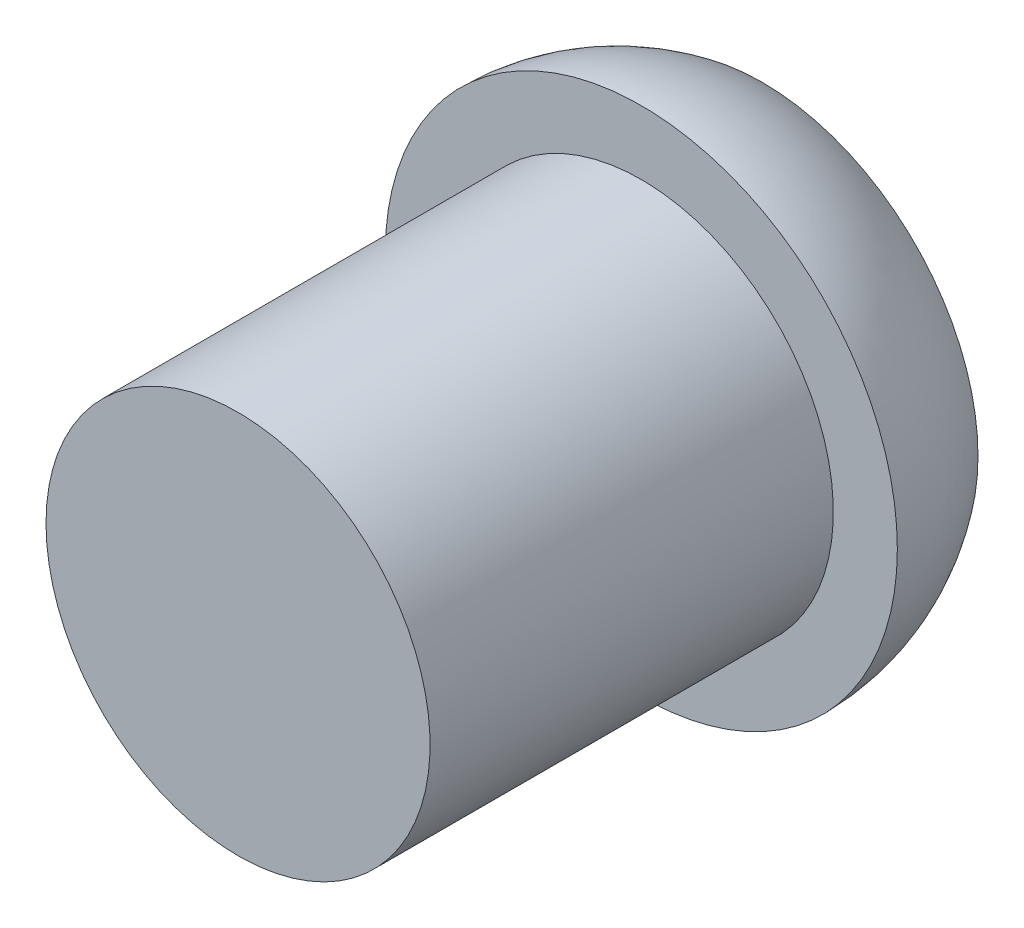
SolidWorks part; units mm, degrees
material "ABS"
ref_plane "Ground_Plane" through (0, 0, 0) normal (0, 0, 1) x (1, 0, 0)
ref_plane "VehicleCentre_Plane" through (0, 0, 0) normal (0, 1, 0) x (1, 0, 0)
ref_plane "FrontAxle_Plane" through (0, 0, 0) normal (1, 0, 0) x (0, 0, -1)
sketch "Sketch1" plane through (0, 0, 0) normal (0, 1, 0) x (1, 0, 0)
  line L0 (0, -10) -> (4.7625, -10)
  line L1 (4.7625, -10) -> (4.7625, 0)
  line L2 (4.7625, 0) -> (6.35, 0)
  line L3 (5.35, 3) -> (3.4641, 3)
  line L4 (0, 5) -> (0, -10)
  arc A0 (6.35, 0) -> (5.35, 3) centre (1.35, 0) ccw
  arc A1 (3.4641, 3) -> (0, 5) centre (0, 1) ccw
  dimension "D4" = 5
  dimension "D5" = 2
  dimension "D6" = 4
  dimension "D1" = 4.7625
  dimension "D2" = 6.35
  dimension "D3" = 3
  dimension "D7" = 10
revolve "Revolve1" add sketch "Sketch1" angle 360 about L4
